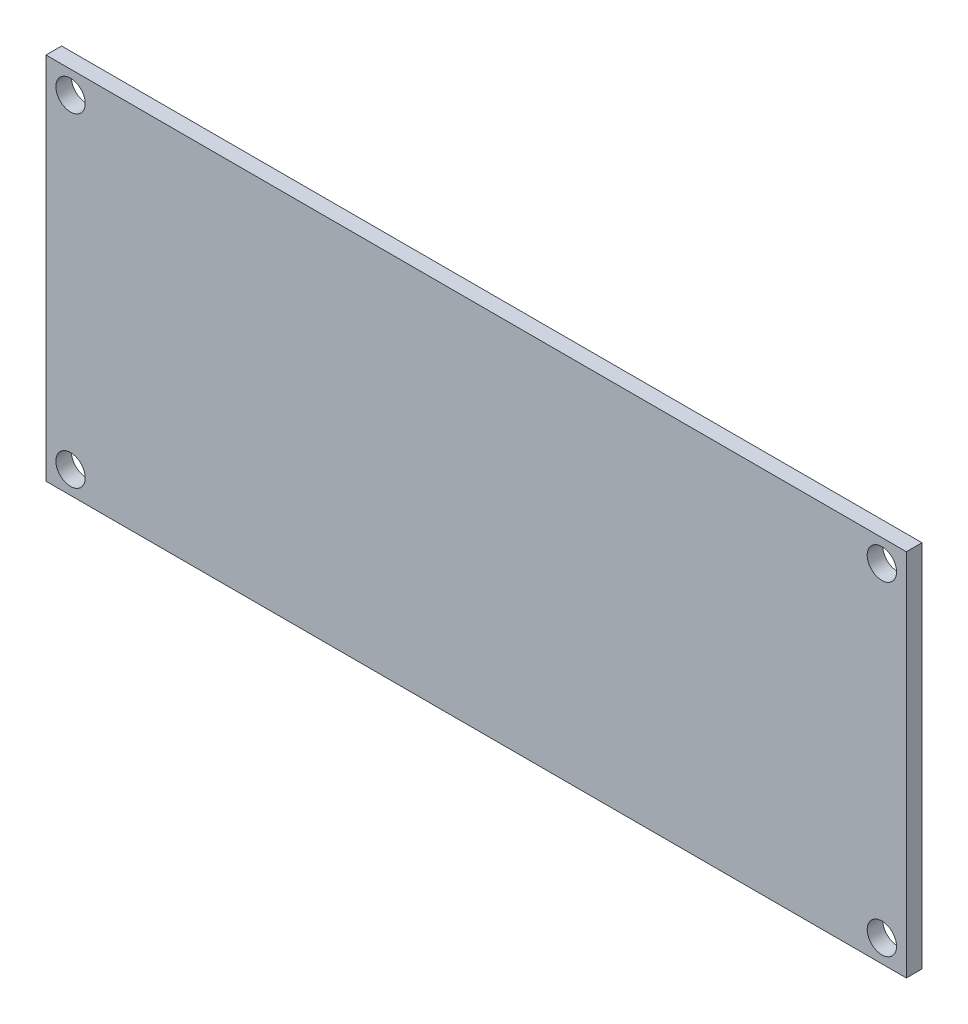
SolidWorks part; units mm, degrees
ref_plane "Front Plane" through (0, 0, 0) normal (0, 0, 1) x (1, 0, 0)
ref_plane "Top Plane" through (0, 0, 0) normal (0, 1, 0) x (1, 0, 0)
ref_plane "Right Plane" through (0, 0, 0) normal (1, 0, 0) x (0, 0, -1)
sketch "Sketch1" plane through (0, 0, 0) normal (0, 0, 1) x (1, 0, 0)
  line L0 (1.9939, 28.2194) -> (68.0339, 28.2194) construction
  line L1 (0, 0) -> (70.0278, 0)
  line L2 (0, 0) -> (0, 30.0482)
  line L3 (0, 30.0482) -> (70.0278, 30.0482)
  line L4 (70.0278, 0) -> (70.0278, 30.0482)
  line L5 (68.0339, 28.2194) -> (68.0339, 1.8288) construction
  line L6 (68.0339, 1.8288) -> (1.9939, 1.8288) construction
  line L7 (1.9939, 1.8288) -> (1.9939, 28.2194) construction
  line L8 (1.9939, 15.0241) -> (0, 15.0241) construction
  line L9 (35.0139, 30.0482) -> (35.0139, 28.2194) construction
  circle A0 centre (1.9939, 28.2194) radius 1.1938
  circle A1 centre (68.0339, 28.2194) radius 1.1938
  circle A2 centre (1.9939, 1.8288) radius 1.1938
  circle A3 centre (68.0339, 1.8288) radius 1.1938
  dimension "D3" = 2.3876
  dimension "D1" = 30.0482
  dimension "D2" = 70.0278
  dimension "D4" = 26.3906
  dimension "D5" = 66.04
extrude "Boss-Extrude1" add sketch "Sketch1" along normal blind 1.27
